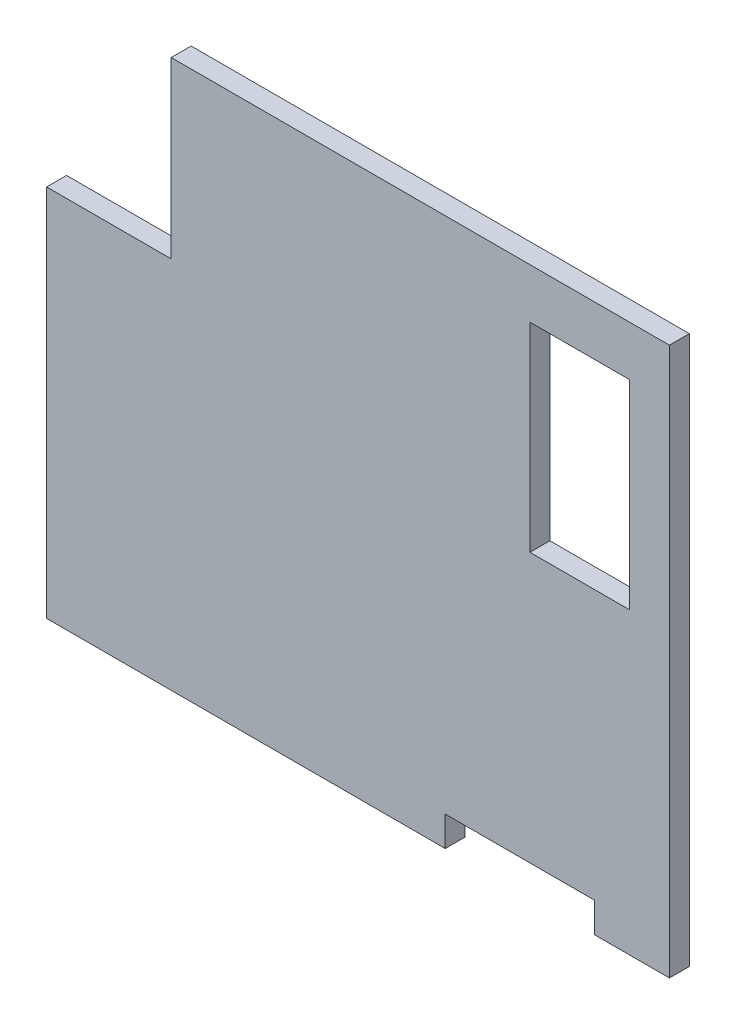
SolidWorks part; units mm, degrees
ref_plane "Ebene vorne" through (0, 0, 0) normal (0, 0, 1) x (1, 0, 0)
ref_plane "Ebene oben" through (0, 0, 0) normal (0, 1, 0) x (1, 0, 0)
ref_plane "Ebene rechts" through (0, 0, 0) normal (1, 0, 0) x (0, 0, -1)
sketch "Skizze1" plane through (0, 0, 0) normal (0, 0, 1) x (1, 0, 0)
  line L0 (0, 0) -> (80, 0)
  line L1 (80, 0) -> (80, 6)
  line L2 (80, 6) -> (110, 6)
  line L3 (110, 6) -> (110, 0)
  line L4 (110, 0) -> (125, 0)
  line L5 (125, 0) -> (125, 110)
  line L6 (125, 110) -> (25, 110)
  line L7 (25, 110) -> (25, 75)
  line L8 (25, 75) -> (0, 75)
  line L9 (0, 75) -> (0, 0)
  line L10 (117, 100) -> (97, 100)
  line L11 (97, 100) -> (97, 60)
  line L12 (97, 60) -> (117, 60)
  line L13 (117, 60) -> (117, 100)
  dimension "D1" = 15
  dimension "D2" = 30
  dimension "D3" = 125
  dimension "D4" = 6
  dimension "D5" = 110
  dimension "D6" = 40
  dimension "D7" = 60
  dimension "D8" = 20
  dimension "D9" = 8
  dimension "D10" = 100
  dimension "D11" = 75
extrude "Aufsatz-Linear austragen1" add sketch "Skizze1" along normal blind 4
